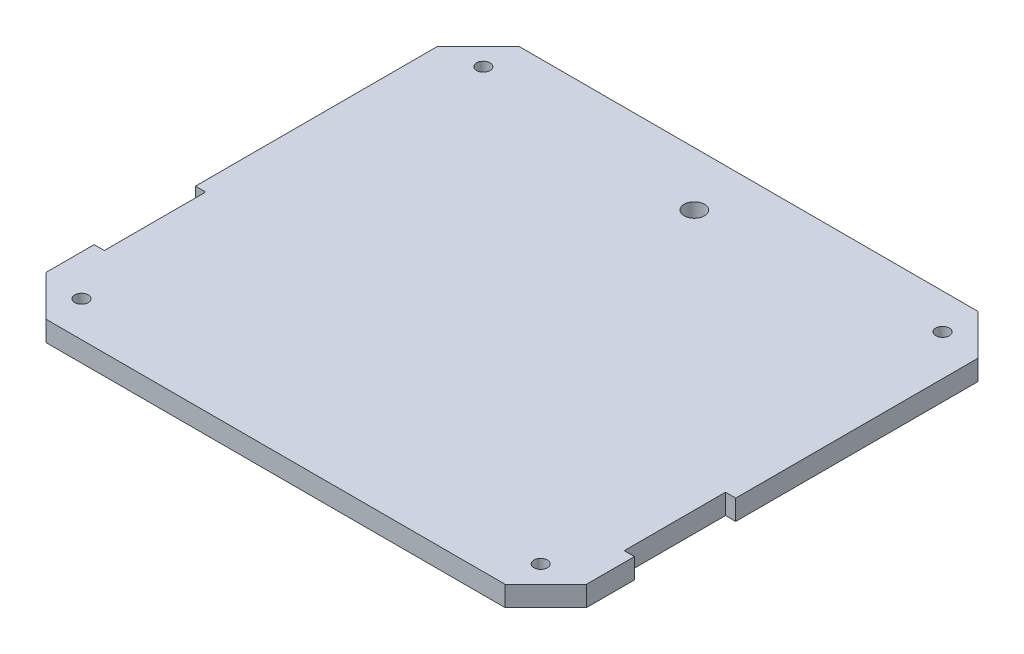
SolidWorks part; units mm, degrees
ref_plane "Front Plane" through (0, 0, 0) normal (0, 0, 1) x (1, 0, 0)
ref_plane "Top Plane" through (0, 0, 0) normal (0, 1, 0) x (1, 0, 0)
ref_plane "Right Plane" through (0, 0, 0) normal (1, 0, 0) x (0, 0, -1)
sketch "Sketch1" plane through (0, 0, 0) normal (0, 1, 0) x (1, 0, 0)
  line L0 (0, 175) -> (0, -175) construction
  line L1 (-200, -175) -> (200, -175)
  line L2 (-200, -175) -> (-200, -109.3684)
  line L3 (-200, 175) -> (200, 175)
  line L4 (200, -175) -> (200, -109.3684)
  line L5 (-200, -175) -> (200, 175) construction
  line L6 (-200, 175) -> (200, -175) construction
  line L7 (-200, 0) -> (200, 0) construction
  line L8 (-200, -34.3684) -> (-200, 175)
  line L13 (-192.447, -109.3684) -> (-200, -109.3684)
  line L14 (-192.447, -109.3684) -> (-192.447, -34.3684)
  line L15 (-192.447, -34.3684) -> (-200, -34.3684)
  line L17 (-192.447, -109.3684) -> (-200, -75) construction
  line L18 (-192.447, -34.3684) -> (-200, -75) construction
  line L19 (192.447, -109.3684) -> (200, -109.3684)
  line L20 (192.447, -109.3684) -> (192.447, -34.3684)
  line L21 (192.447, -34.3684) -> (200, -34.3684)
  line L22 (200, -34.3684) -> (200, 175)
  point P0 (0, 0)
  point P18 (0, 157.5)
  point P19 (-200, -75)
  dimension "D1" = 350
  dimension "D2" = 400
  dimension "D5" = 75
  dimension "D7" = 75
extrude "Boss-Extrude1" add sketch "Sketch1" along normal blind 15
sketch "Sketch4" plane through (0, 15, 0) normal (0, 1, 0) x (1, 0, 0)
  line L0 (-170, 175) -> (-200, 145)
  line L1 (-200, 175) -> (200, 175) construction
  line L2 (-200, -34.3684) -> (-200, 175) construction
  line L3 (-200, 145) -> (-200, 175)
  line L4 (-200, 175) -> (-170, 175)
  line L5 (0, 175) -> (0, -175) construction
  line L6 (-200, -175) -> (200, -175) construction
  line L7 (-200, 0) -> (200, 0) construction
  line L8 (200, -34.3684) -> (200, 175) construction
  line L9 (-200, -145) -> (-200, -175)
  line L10 (-170, -175) -> (-200, -145)
  line L11 (-200, -175) -> (-170, -175)
  line L12 (170, -175) -> (200, -145)
  line L13 (200, -175) -> (170, -175)
  line L14 (200, -145) -> (200, -175)
  line L15 (200, 145) -> (200, 175)
  line L16 (170, 175) -> (200, 145)
  line L17 (200, 175) -> (170, 175)
  line L18 (-200, 175) -> (200, -175) construction
  line L19 (200, 175) -> (-200, -175) construction
  circle A0 centre (-170, 148.75) radius 5
  circle A1 centre (170, 148.75) radius 5
  circle A2 centre (170, -148.75) radius 5
  circle A3 centre (-170, -148.75) radius 5
  dimension "D3" = 10
  dimension "D1" = 30
  dimension "D2" = 30
  dimension "D4" = 30
extrude "Cut-Extrude1" cut sketch "Sketch4" against normal through all
sketch "Sketch5" plane through (0, 0, 0) normal (0, -1, 0) x (1, 0, 0)
  line L0 (0, 175) -> (0, -175) construction
  line L1 (-170, 175) -> (170, 175) construction
  line L2 (-170, -175) -> (170, -175) construction
  circle A0 centre (0, -135) radius 7.5
  dimension "D1" = 15
  dimension "D2" = 40
extrude "Cut-Extrude2" cut sketch "Sketch5" against normal through all
